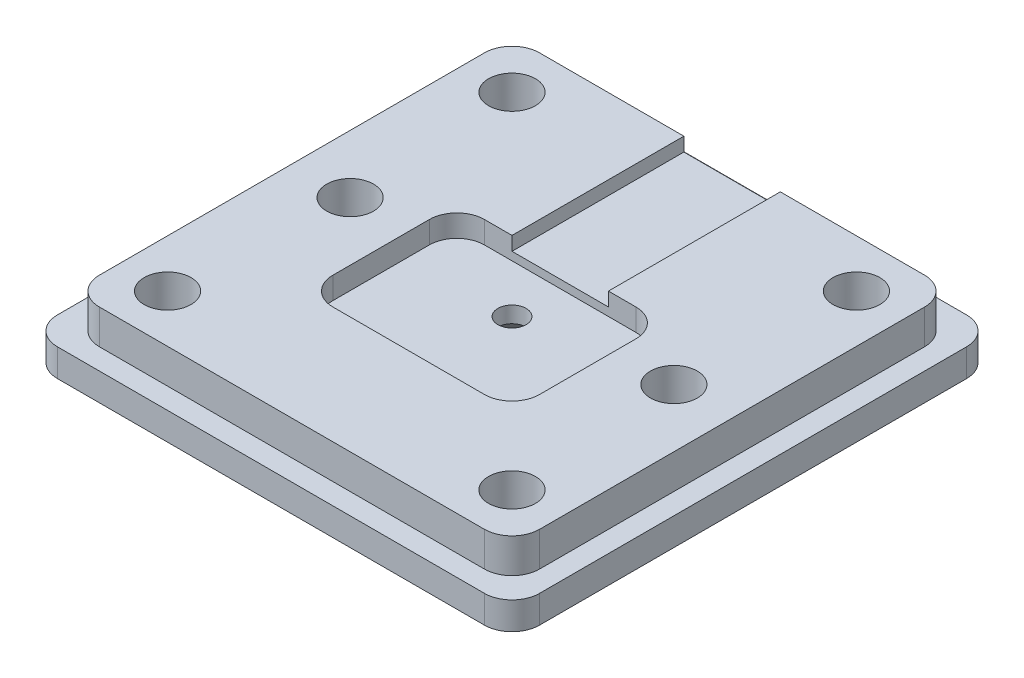
SolidWorks part; units mm, degrees
material "3.1355 (EN-AW 2024)"
ref_plane "Спереди" through (0, 0, 0) normal (0, 0, 1) x (1, 0, 0)
ref_plane "Сверху" through (0, 0, 0) normal (0, 1, 0) x (1, 0, 0)
ref_plane "Справа" through (0, 0, 0) normal (1, 0, 0) x (0, 0, -1)
sketch "Эскиз1" plane through (0, 0, 0) normal (0, 1, 0) x (1, 0, 0)
  line L1 (-13.975, 15.975) -> (13.975, 15.975)
  line L2 (-15.975, 13.975) -> (-15.975, -13.975)
  line L3 (-13.975, -15.975) -> (13.975, -15.975)
  line L4 (15.975, 13.975) -> (15.975, -13.975)
  arc A0 (-15.975, -13.975) -> (-13.975, -15.975) centre (-13.975, -13.975) ccw
  arc A1 (13.975, -15.975) -> (15.975, -13.975) centre (13.975, -13.975) ccw
  arc A2 (13.975, 15.975) -> (15.975, 13.975) centre (13.975, 13.975) cw
  arc A3 (-13.975, 15.975) -> (-15.975, 13.975) centre (-13.975, 13.975) ccw
  point P6 (-15.975, -15.975)
  point P9 (15.975, -15.975)
  point P15 (0, 15.975)
  point P16 (-15.975, 0)
  dimension "D2" = 2
  dimension "D1" = 31.95
extrude "Бобышка-Вытянуть1" add sketch "Эскиз1" along normal blind 2.5
sketch "Эскиз9" plane through (0, 0, 0) normal (0, -1, 0) x (1, 0, 0)
  line L1 (-15.5, 17.5) -> (15.5, 17.5)
  line L2 (-17.5, 15.5) -> (-17.5, -15.5)
  line L3 (-15.5, -17.5) -> (15.5, -17.5)
  line L4 (17.5, 15.5) -> (17.5, -15.5)
  line L5 (-17.5, 17.5) -> (17.5, -17.5) construction
  line L6 (-17.5, -17.5) -> (17.5, 17.5) construction
  arc A0 (-17.5, -15.5) -> (-15.5, -17.5) centre (-15.5, -15.5) ccw
  arc A1 (15.5, -17.5) -> (17.5, -15.5) centre (15.5, -15.5) ccw
  arc A2 (15.5, 17.5) -> (17.5, 15.5) centre (15.5, 15.5) cw
  arc A3 (-15.5, 17.5) -> (-17.5, 15.5) centre (-15.5, 15.5) ccw
  point P0 (0, 0)
  dimension "D3" = 2
  dimension "D1" = 35
  dimension "D2" = 35
extrude "Бобышка-Вытянуть2" add sketch "Эскиз9" along normal blind 2
hole_wizard "Диаметр отверстия Ø3.4" positions "Эскиз3" profile "Эскиз2" hole size "Ø3.4" standard "ISO" end condition through all
sketch "Эскиз3" plane through (0, -2, 0) normal (0, 1, 0) x (1, 0, 0)
  line L14 (-12.5, 12.5) -> (-17.5, 12.5) construction
  line L15 (-17.5, -15.5) -> (-17.5, 15.5) construction
  line L18 (-12.5, 12.5) -> (-12.5, 17.5) construction
  line L19 (-15.5, 17.5) -> (15.5, 17.5) construction
  line L22 (12.5, 12.5) -> (17.5, 12.5) construction
  line L23 (17.5, 15.5) -> (17.5, -15.5) construction
  line L31 (-12.5, -12.5) -> (-12.5, -17.5) construction
  line L32 (15.5, -17.5) -> (-15.5, -17.5) construction
  point P0 (-12.5, 12.5)
  point P2 (12.5, 12.5)
  point P4 (12.5, -12.5)
  point P6 (-12.5, -12.5)
  dimension "D1" = 5
sketch "Эскиз2" plane through (-12.5, -2, -12.5) normal (1, 0, 0) x (0, 0, -1)
  line L0 (0, 0) -> (0, 4.5)
  line L1 (0, 4.5) -> (1.7, 4.5)
  line L2 (1.7, 4.5) -> (1.7, 0)
  line L5 (1.7, 0) -> (0, 0)
  line L11 (0, -6.35) -> (0, 107.95) construction
  dimension "Диаметр сквозного отверстия" = 3.4
  dimension "Глубина сквозного отверстия" = 4.5
sketch "Эскиз4" plane through (0, 2.5, 0) normal (0, 1, 0) x (1, 0, 0)
  line L1 (-5.5, 3.5) -> (5.5, 3.5)
  line L2 (-7.5, 1.5) -> (-7.5, -5.5)
  line L3 (-5.5, -7.5) -> (5.5, -7.5)
  line L4 (7.5, 1.5) -> (7.5, -5.5)
  arc A0 (-7.5, -5.5) -> (-5.5, -7.5) centre (-5.5, -5.5) ccw
  arc A1 (5.5, -7.5) -> (7.5, -5.5) centre (5.5, -5.5) ccw
  arc A2 (5.5, 3.5) -> (7.5, 1.5) centre (5.5, 1.5) cw
  arc A3 (-5.5, 3.5) -> (-7.5, 1.5) centre (-5.5, 1.5) ccw
  point P0 (0, 0)
  point P1 (0, 3.5)
  dimension "D4" = 3.5
  dimension "D3" = 2
  dimension "D1" = 15
  dimension "D2" = 11
extrude "Вырез Платы" cut sketch "Эскиз4" against normal blind 1.6
hole_wizard "Крепление дна М3" positions "Эскиз6" profile "Эскиз5" countersink size "M3" standard "ISO" end condition through all
sketch "Эскиз6" plane through (0, -2, 0) normal (0, -1, 0) x (-1, 0, 0)
  line L16 (11.75, 0) -> (0, 0) construction
  line L17 (0, 0) -> (-11.75, 0) construction
  point P0 (11.75, 0)
  point P2 (-11.75, 0)
  dimension "D1" = 11.75
sketch "Эскиз5" plane through (-11.75, -2, 0) normal (1, 0, 0) x (0, 0, -1)
  line L0 (0, 0) -> (0, 4.5)
  line L1 (0, 4.5) -> (1.7, 4.5)
  line L2 (1.7, 4.5) -> (1.7, 1.45)
  line L3 (1.7, 1.45) -> (3.15, 0)
  line L5 (3.15, 0) -> (0, 0)
  line L6 (-1.7, 1.45) -> (-3.15, 0) construction
  line L11 (0, -6.35) -> (0, 107.95) construction
  dimension "Диаметр сквозного отверстия" = 3.4
  dimension "Глубина сквозного отверстия" = 4.5
  dimension "Диаметр передней зенковки" = 6.3
  dimension "Угол передней зенковки" = 90
sketch "Эскиз8" plane through (0, 2.5, 0) normal (0, 1, 0) x (1, 0, 0)
  line L0 (13.975, 15.975) -> (-13.975, 15.975) construction
  line L1 (-3.5, 3.5) -> (3.5, 3.5)
  line L2 (-3.5, 3.5) -> (-3.5, 15.975)
  line L3 (-3.5, 15.975) -> (3.5, 15.975)
  line L4 (3.5, 3.5) -> (3.5, 15.975)
  line L5 (5.5, 3.5) -> (-5.5, 3.5) construction
  point P8 (0, 3.5)
  point P11 (0, 3.5)
  dimension "D1" = 7
extrude "Вырез Разъема" cut sketch "Эскиз8" against normal blind 1
sketch "Эскиз11" plane through (0, -2, 0) normal (0, -1, 0) x (1, 0, 0)
  line L1 (-7.5, 7.5) -> (7.5, 7.5) construction
  line L2 (-7.5, 7.5) -> (-7.5, -7.5) construction
  line L3 (-7.5, -7.5) -> (7.5, -7.5) construction
  line L4 (7.5, 7.5) -> (7.5, -7.5) construction
  circle A0 centre (-7.5, 7.5) radius 3.5
  circle A1 centre (7.5, 7.5) radius 3.5
  circle A2 centre (-7.5, -7.5) radius 3.5
  circle A3 centre (7.5, -7.5) radius 3.5
  point P4 (0, 0)
  point P10 (-7.5, 0)
  point P11 (0, 7.5)
  dimension "D1" = 7
  dimension "D2" = 15
extrude "Вырез магнитов 7*1" cut sketch "Эскиз11" against normal blind 1
hole_wizard "Отверстие для настройки M2.5" positions "Эскиз12" profile "Эскиз13" tap size "M2.5" standard "DIN" end condition through all
sketch "Эскиз12" plane through (0, -2, 0) normal (0, -1, 0) x (-1, 0, 0)
  point P0 (0, 0)
sketch "Эскиз13" plane through (0, -2, 0) normal (1, 0, 0) x (0, 0, -1)
  line L0 (0, 0) -> (0, 4.5)
  line L1 (0, 4.5) -> (1.025, 4.5)
  line L2 (1.025, 4.5) -> (1.025, 1.725)
  line L3 (1.025, 1.725) -> (2.75, 0)
  line L5 (2.75, 0) -> (0, 0)
  line L6 (-1.025, 1.725) -> (-2.75, 0) construction
  line L11 (0, -6.35) -> (0, 107.95) construction
  dimension "Диаметр проходного сверла" = 2.05
  dimension "Глубина проходного сверла" = 4.5
  dimension "Диаметр передней зенковки" = 5.5
  dimension "Угол передней зенковки" = 90
